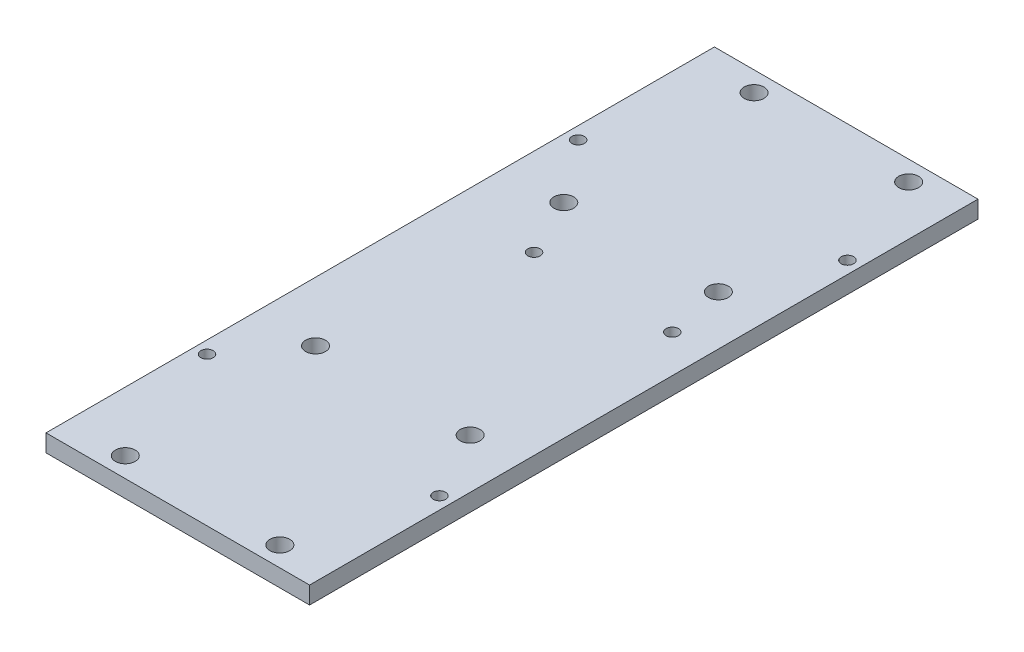
SolidWorks part; units mm, degrees
material "PBT General Purpose"
ref_plane "Front Plane" through (0, 0, 0) normal (0, 0, 1) x (1, 0, 0)
ref_plane "Top Plane" through (0, 0, 0) normal (0, 1, 0) x (1, 0, 0)
ref_plane "Right Plane" through (0, 0, 0) normal (1, 0, 0) x (0, 0, -1)
sketch "Sketch1" plane through (0, 0, 0) normal (0, 1, 0) x (1, 0, 0)
  line L0 (-50.7, 30) -> (-2.5, 30) construction
  line L1 (-2.5, 30) -> (-2.5, 28.7) construction
  line L2 (-50.7, 104.9) -> (-50.7, 30) construction
  line L3 (-2.5, 111.05) -> (-2.5, 28.7) construction
  line L4 (-35.5, 80.8) -> (-7.6, 80.8) construction
  line L5 (-53.2, 134.9) -> (0, 134.9)
  line L6 (-53.2, 134.9) -> (-53.2, 0)
  line L7 (-53.2, 0) -> (0, 0)
  line L8 (0, 134.9) -> (0, 0)
  circle A0 centre (-50.7, 104.9) radius 1.25
  circle A1 centre (-2.5, 111.05) radius 1.25
  circle A2 centre (-35.5, 80.8) radius 1.25
  circle A3 centre (-7.6, 80.8) radius 1.25
  circle A4 centre (-50.7, 30) radius 1.25
  circle A5 centre (-2.5, 28.7) radius 1.25
  dimension "D1" = 2.5
  dimension "D2" = 48.2
  dimension "D3" = 1.3
  dimension "D4" = 82.35
  dimension "D5" = 74.9
  dimension "D6" = 50.8
  dimension "D7" = 15.2
  dimension "D8" = 27.9
  dimension "D9" = 30
  dimension "D10" = 30
  dimension "D11" = 2.5
  dimension "D12" = 2.5
extrude "Boss-Extrude1" add sketch "Sketch1" along normal blind 3.5
sketch "Pololu Mounting Bracket" plane through (0, 3.5, 0) normal (0, 1, 0) x (1, 0, 0)
  line L0 (-53.2, 0) -> (0, 0) construction
  circle A0 centre (-41.2, 4) radius 2
  circle A1 centre (-10, 4) radius 2
  circle A2 centre (-41.2, 42.4) radius 2
  circle A3 centre (-10, 42.4) radius 2
  circle A4 centre (-41.2, 130.9) radius 2
  circle A5 centre (-10, 130.9) radius 2
  circle A6 centre (-10, 92.5) radius 2
  circle A7 centre (-41.2, 92.5) radius 2
  point P4 (-26.6, 0)
  dimension "D1" = 4
  dimension "D2" = 31.2
  dimension "D4" = 4
  dimension "D5" = 38.4
  dimension "D3" = 16.6
extrude "Pololu 37mm mounting bracket holes" cut sketch "Pololu Mounting Bracket" against normal through all
